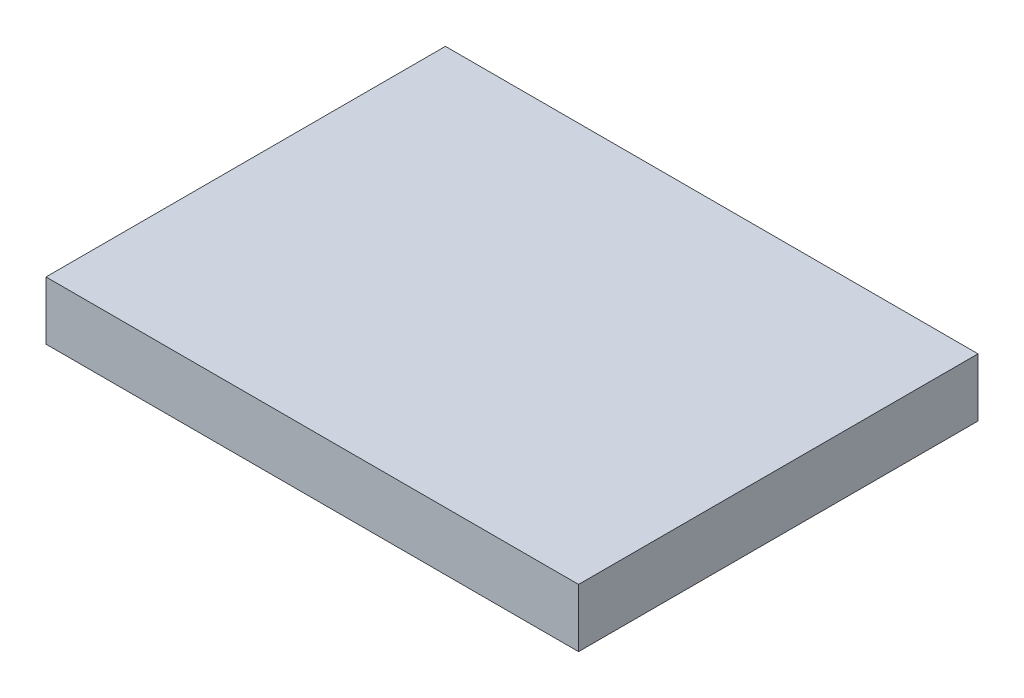
SolidWorks part; units mm, degrees
ref_plane "Front Plane" through (0, 0, 0) normal (0, 0, 1) x (1, 0, 0)
ref_plane "Top Plane" through (0, 0, 0) normal (0, 1, 0) x (1, 0, 0)
ref_plane "Right Plane" through (0, 0, 0) normal (1, 0, 0) x (0, 0, -1)
sketch "Sketch1" plane through (0, 0, 0) normal (0, 1, 0) x (1, 0, 0)
  line L5 (45.72, -34.29) -> (-45.72, -34.29)
  line L6 (45.72, -34.29) -> (45.72, 34.29)
  line L7 (45.72, 34.29) -> (-45.72, 34.29)
  line L8 (-45.72, -34.29) -> (-45.72, 34.29)
  line L9 (0, 34.29) -> (0, -34.29) construction
  line L10 (45.72, 0) -> (-45.72, 0) construction
  point P0 (0, 0)
  point P5 (0, 0)
  dimension "D1" = 68.58
  dimension "D2" = 91.44
extrude "Boss-Extrude1" add sketch "Sketch1" along normal blind 10
